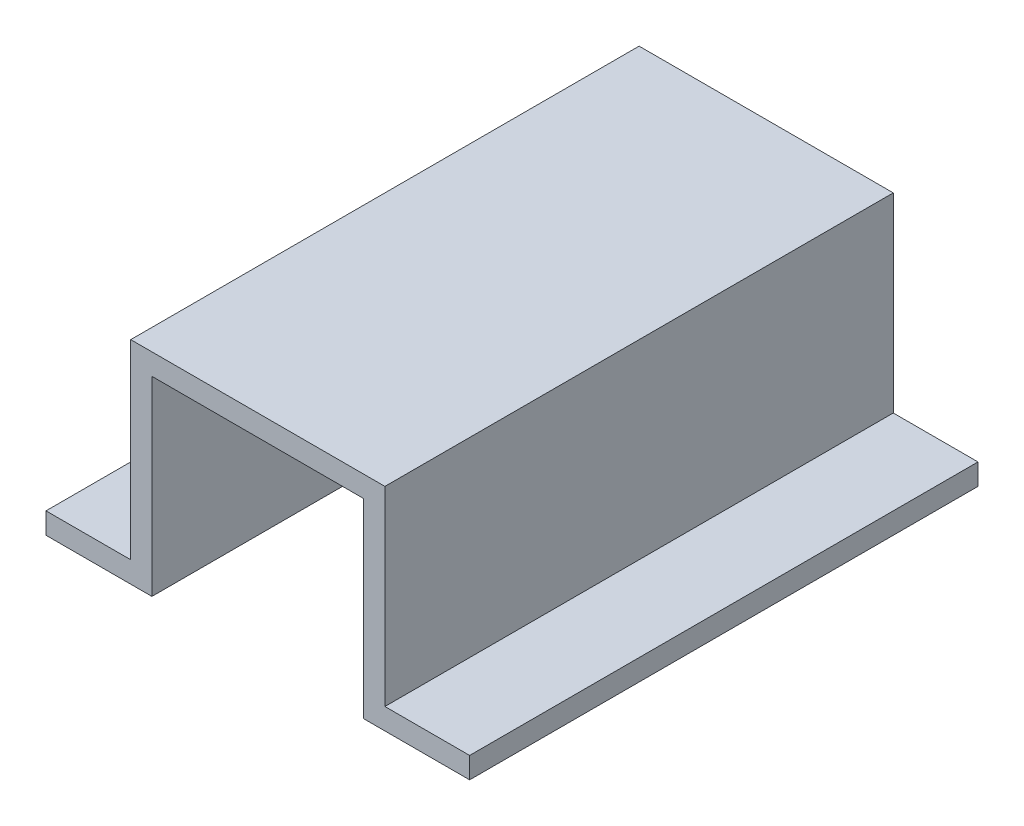
SolidWorks part; units mm, degrees
ref_plane "Front Plane" through (0, 0, 0) normal (0, 0, 1) x (1, 0, 0)
ref_plane "Top Plane" through (0, 0, 0) normal (0, 1, 0) x (1, 0, 0)
ref_plane "Right Plane" through (0, 0, 0) normal (1, 0, 0) x (0, 0, -1)
sketch "Sketch1" plane through (0, 0, 0) normal (0, 0, 1) x (1, 0, 0)
  line L0 (5, 0) -> (5, 9)
  line L1 (5, 9) -> (-5, 9)
  line L3 (-6, 10) -> (6, 10)
  line L4 (6, 10) -> (6, 1)
  line L6 (0, 24.2784) -> (0, -14.4845) construction
  line L10 (-10, 0) -> (-10, 1)
  line L11 (5, 0) -> (10, 0)
  line L13 (6, 1) -> (10, 1)
  line L14 (10, 0) -> (10, 1)
  line L15 (-6, 1) -> (-10, 1)
  line L16 (-5, 0) -> (-10, 0)
  line L17 (-6, 10) -> (-6, 1)
  line L18 (-5, 0) -> (-5, 9)
  point P7 (9.049, 1)
  point P11 (0, 9)
  point P12 (0, 10)
  point P13 (5.1592, 0)
  point P20 (0, 10)
  point P21 (0, 9)
  dimension "D1" = 1
  dimension "D2" = 10
  dimension "D3" = 20
  dimension "D4" = 1
  dimension "D5" = 1
  dimension "D6" = 9
extrude "Boss-Extrude1" add sketch "Sketch1" along normal blind 24
